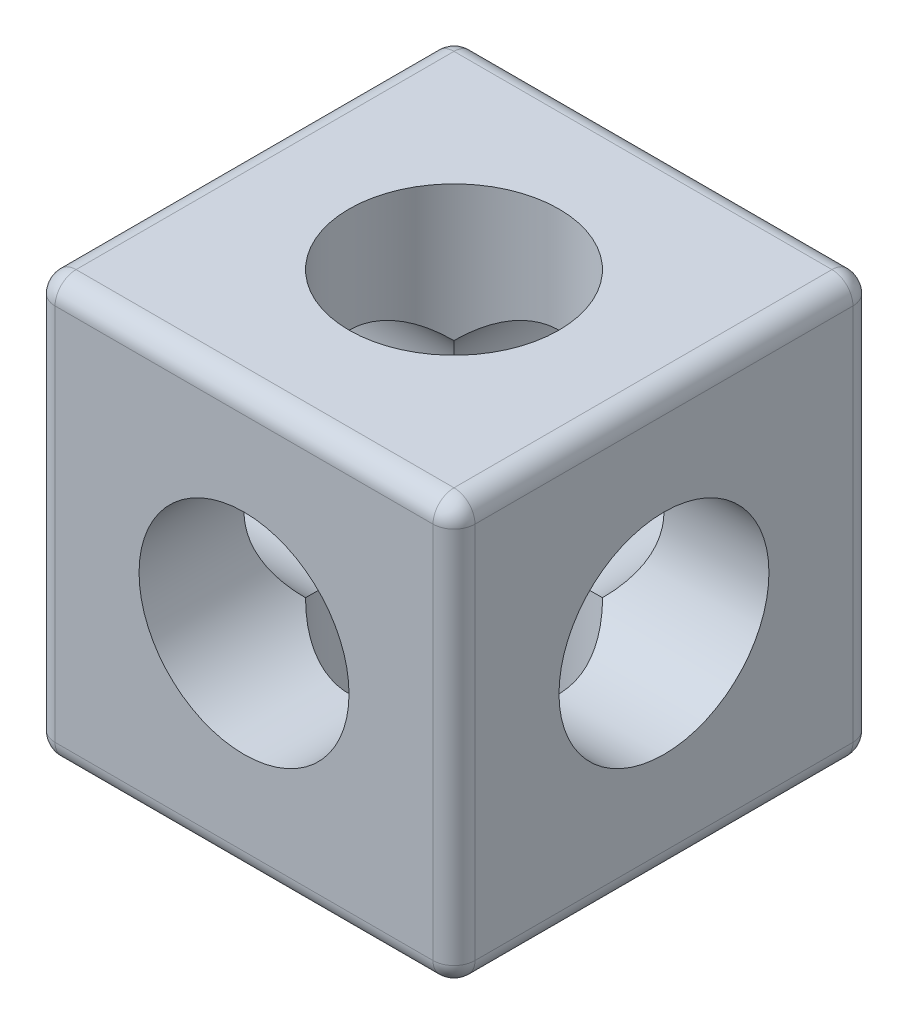
SolidWorks part; units mm, degrees
ref_plane "Front Plane" through (0, 0, 0) normal (0, 0, 1) x (1, 0, 0)
ref_plane "Top Plane" through (0, 0, 0) normal (0, 1, 0) x (1, 0, 0)
ref_plane "Right Plane" through (0, 0, 0) normal (1, 0, 0) x (0, 0, -1)
sketch "Sketch1" plane through (0, 0, 0) normal (0, 0, 1) x (1, 0, 0)
  line L1 (2, 2) -> (-2, 2)
  line L2 (2, 2) -> (2, -2)
  line L3 (2, -2) -> (-2, -2)
  line L4 (-2, 2) -> (-2, -2)
  line L5 (2, 2) -> (-2, -2) construction
  line L6 (2, -2) -> (-2, 2) construction
  point P0 (0, 0)
  dimension "D1" = 4
  dimension "D2" = 4
extrude "Boss-Extrude1" add sketch "Sketch1" along normal blind 4
sketch "Sketch2" plane through (0, 2, 0) normal (0, 1, 0) x (1, 0, 0)
  line L0 (-2, -4) -> (2, 0) construction
  line L1 (-2, 0) -> (2, -4) construction
  circle A0 centre (0, -2) radius 1
  point P10 (0, 0)
  point P11 (0, -2)
  dimension "D1" = 2
extrude "Cut-Extrude1" cut sketch "Sketch2" against normal up to next
sketch "Sketch3" plane through (0, 0, 4) normal (0, 0, 1) x (1, 0, 0)
  line L0 (2, 2) -> (-2, -2) construction
  line L1 (-2, -2) -> (-2, 2) construction
  line L2 (-2, 2) -> (-2, -2) construction
  line L3 (2, 2) -> (-2, 2) construction
  line L4 (-2, 2) -> (2, -2) construction
  circle A0 centre (0, 0) radius 1
extrude "Cut-Extrude2" cut sketch "Sketch3" against normal through all
sketch "Sketch4" plane through (2, 0, 0) normal (1, 0, 0) x (0, 0, -1)
  line L0 (0, 2) -> (-4, -2) construction
  line L1 (-4, -2) -> (0, -2) construction
  line L2 (0, -2) -> (-4, 2) construction
  circle A0 centre (-2, 0) radius 1
extrude "Cut-Extrude3" cut sketch "Sketch4" against normal through all
fillet "Fillet1" radius 0.2 12 edges at (0, -2, 4) (2, 0, 4) (2, -2, 2) (2, 2, 2) (0, 2, 4) (-2, 0, 4) (2, 0, 0) (0, -2, 0) (-2, -2, 2) (-2, 0, 0) (-2, 2, 2) (0, 2, 0)
